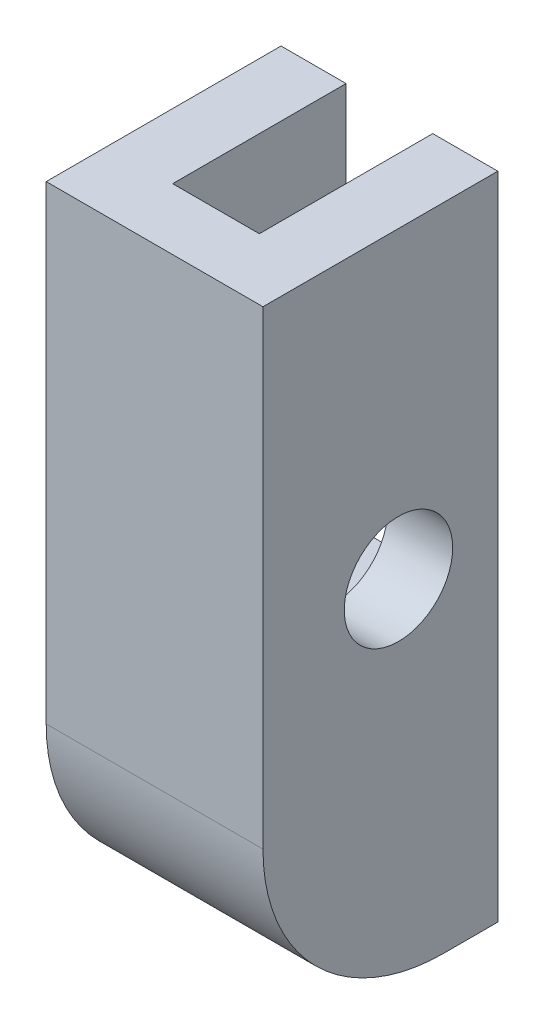
SolidWorks part; units mm, degrees
ref_plane "Front Plane" through (0, 0, 0) normal (0, 0, 1) x (1, 0, 0)
ref_plane "Top Plane" through (0, 0, 0) normal (0, 1, 0) x (1, 0, 0)
ref_plane "Right Plane" through (0, 0, 0) normal (1, 0, 0) x (0, 0, -1)
sketch "Sketch2" plane through (0, 0, 0) normal (1, 0, 0) x (0, 0, -1)
  line L1 (-8.255, -22.86) -> (8.255, -22.86)
  line L2 (-8.255, -22.86) -> (-8.255, 22.86)
  line L3 (-8.255, 22.86) -> (8.255, 22.86)
  line L4 (8.255, -22.86) -> (8.255, 22.86)
  line L5 (-8.255, -22.86) -> (8.255, 22.86) construction
  line L6 (-8.255, 22.86) -> (8.255, -22.86) construction
  point P0 (0, 0)
  dimension "D1" = 16.51
  dimension "D2" = 45.72
extrude "Boss-Extrude1" add sketch "Sketch2" along normal mid plane 15.24
fillet "Fillet1" radius 12.7 1 edges at (0, -22.86, 8.255)
sketch "Sketch3" plane through (0, 0, -8.255) normal (0, 0, -1) x (-1, 0, 0)
  line L0 (-7.62, 22.86) -> (7.62, 22.86) construction
  line L1 (-3.048, 22.86) -> (3.048, 22.86)
  line L2 (-3.048, 22.86) -> (-3.048, -3.81)
  line L3 (-3.048, -3.81) -> (3.048, -3.81)
  line L4 (3.048, 22.86) -> (3.048, -3.81)
  dimension "D1" = 26.67
  dimension "D2" = 6.096
  dimension "D3" = 3.048
extrude "Cut-Extrude1" cut sketch "Sketch3" against normal blind 12.192
sketch "Sketch4" plane through (7.62, 0, 0) normal (1, 0, 0) x (0, 0, -1)
  line L0 (8.255, -22.86) -> (8.255, 22.86) construction
  line L1 (-3.937, -3.81) -> (8.255, -3.81) construction
  circle A0 centre (1.27, 1.524) radius 3.81
  dimension "D1" = 6.985
  dimension "D3" = 7.62
  dimension "D2" = 5.334
extrude "Cut-Extrude2" cut sketch "Sketch4" against normal through all
